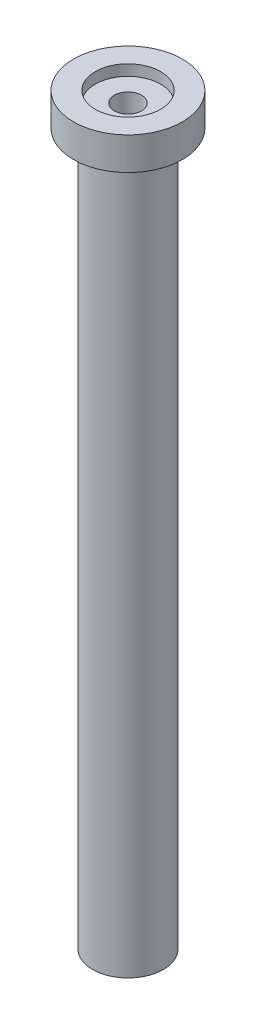
SolidWorks part; units mm, degrees
ref_plane "Front Plane" through (0, 0, 0) normal (0, 0, 1) x (1, 0, 0)
ref_plane "Top Plane" through (0, 0, 0) normal (0, 1, 0) x (1, 0, 0)
ref_plane "Right Plane" through (0, 0, 0) normal (1, 0, 0) x (0, 0, -1)
sketch "Sketch1" plane through (0, 0, 0) normal (0, 1, 0) x (1, 0, 0)
  circle A0 centre (0, 0) radius 3.25
  dimension "D1" = 6.5
extrude "Boss-Extrude1" add sketch "Sketch1" along normal blind 65.3
sketch "Sketch2" plane through (0, 65.3, 0) normal (0, 1, 0) x (1, 0, 0)
  circle A0 centre (0, 0) radius 5
  dimension "D1" = 10
extrude "Boss-Extrude2" add sketch "Sketch2" along normal blind 3
sketch "Sketch3" plane through (0, 0, 0) normal (0, -1, 0) x (1, 0, 0)
  circle A0 centre (0, 0) radius 1.425
  dimension "D1" = 2.85
extrude "Cut-Extrude1" cut sketch "Sketch3" against normal blind 9
shell "Shell1" thickness 2
